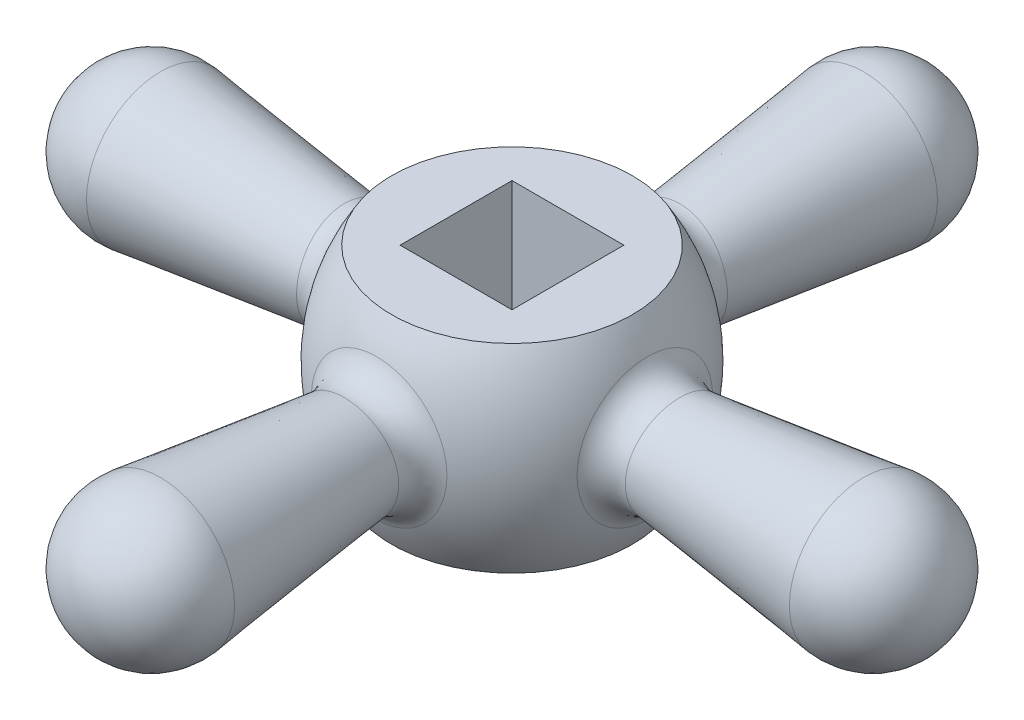
SolidWorks part; units mm, degrees
ref_plane "Front Plane" through (0, 0, 0) normal (0, 0, 1) x (1, 0, 0)
ref_plane "Top Plane" through (0, 0, 0) normal (0, 1, 0) x (1, 0, 0)
ref_plane "Right Plane" through (0, 0, 0) normal (1, 0, 0) x (0, 0, -1)
sketch "Sketch1" plane through (0, 0, 0) normal (1, 0, 0) x (0, 0, -1)
  line L0 (0, -8) -> (0, 8)
  line L1 (0, 8) -> (-9.6886, 8)
  line L2 (0, -8) -> (-9.6886, -8)
  line L3 (0, 0) -> (19.4318, 0) construction
  line L4 (0, 0) -> (0, 22.4965) construction
  arc A0 (-9.6886, 8) -> (-9.6886, -8) centre (3, 0) ccw
  point P6 (0, 0)
  point P10 (-9.6644, 8)
  point P11 (-7.5958, 8)
  point P12 (-9.6886, 8)
  dimension "D1" = 15
  dimension "D2" = 12
  dimension "D3" = 16
revolve "Revolve1" add sketch "Sketch1" angle 360 about L4
sketch "Sketch2" plane through (0, 0, 0) normal (0, 0, 1) x (1, 0, 0)
  line L0 (0, 0) -> (-35, 0)
  line L1 (0, 0) -> (0, -2.4843)
  line L2 (0, -2.4843) -> (-28.2688, -5.9553)
  arc A1 (-35, 0) -> (-28.2688, -5.9553) centre (-29, 0) ccw
  point P3 (-26.539, 0)
  dimension "D3" = 6
  dimension "D1" = 35
  dimension "D2" = 7
revolve "Revolve2" add sketch "Sketch2" angle 360 about L0
fillet "Fillet1" radius 2.5 1 edges at (-11.4842, 3.8745, 0.3934)
pattern_circular "CirPattern1" count 4 over 360 about axis through (0, 8, 0) along (0, -1, 0) of "Fillet1", "Revolve2"
sketch "Sketch3" plane through (0, 8, 0) normal (0, 1, 0) x (1, 0, 0)
  line L1 (-4.5, -4.5) -> (4.5, -4.5)
  line L2 (-4.5, -4.5) -> (-4.5, 4.5)
  line L3 (-4.5, 4.5) -> (4.5, 4.5)
  line L4 (4.5, -4.5) -> (4.5, 4.5)
  line L5 (-4.5, -4.5) -> (4.5, 4.5) construction
  line L6 (-4.5, 4.5) -> (4.5, -4.5) construction
  point P0 (0, 0)
  dimension "D1" = 9
  dimension "D2" = 9
extrude "Cut-Extrude1" cut sketch "Sketch3" against normal blind 11
sketch "Sketch4" plane through (0, -8, 0) normal (0, -1, 0) x (1, 0, 0)
  circle A0 centre (0, 0) radius 7.5
  dimension "D1" = 15
extrude "Cut-Extrude2" cut sketch "Sketch4" against normal blind 3
sketch "Sketch5" plane through (0, -5, 0) normal (0, -1, 0) x (1, 0, 0)
  circle A0 centre (0, 0) radius 2
  dimension "D1" = 4
extrude "Cut-Extrude3" cut sketch "Sketch5" against normal up to next
